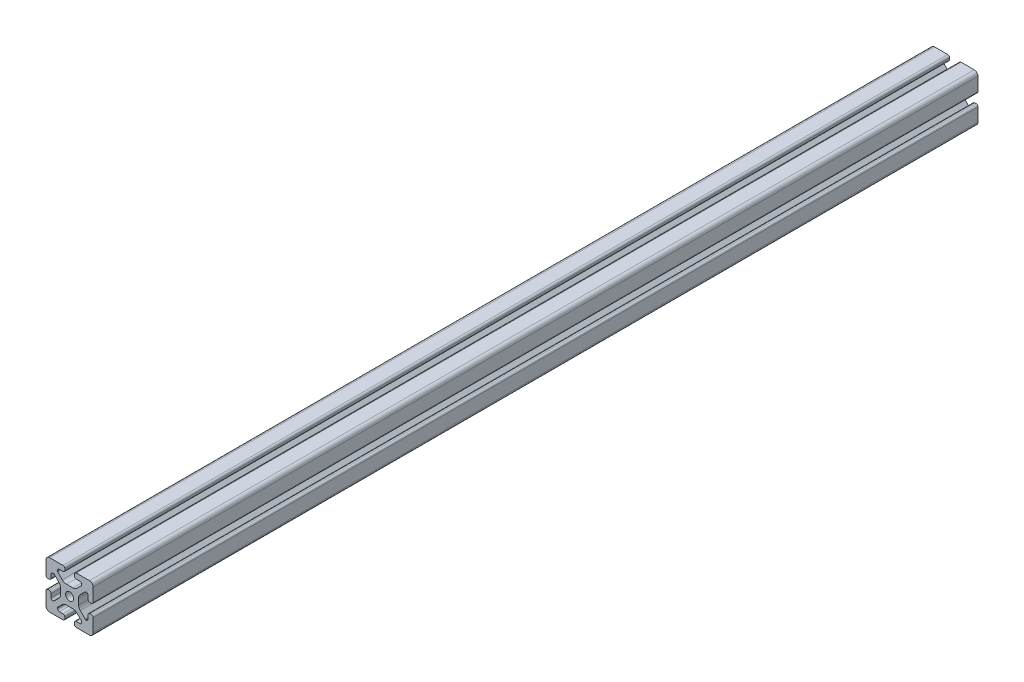
SolidWorks part; units mm, degrees
material "6061 Alloy"
ref_plane "Front Plane" through (0, 0, 0) normal (0, 0, 1) x (1, 0, 0)
ref_plane "Top Plane" through (0, 0, 0) normal (0, 1, 0) x (1, 0, 0)
ref_plane "Right Plane" through (0, 0, 0) normal (1, 0, 0) x (0, 0, -1)
sketch "Sketch1" plane through (0, 0, 0) normal (0, 0, 1) x (1, 0, 0)
  line L0 (0, 19.7407) -> (0, -19.7407) construction
  line L1 (19.0335, 0) -> (-20.7246, 0) construction
  line L2 (-8.715, -15.5246) -> (-5.63, -15.5246)
  line L3 (-10.285, -13.9546) -> (-10.285, -13.4925)
  line L4 (-6.2171, -9.1098) -> (-10.0624, -12.9551)
  line L5 (2.7773, -7.685) -> (-2.7773, -7.685)
  line L6 (10.0624, -12.9551) -> (6.2171, -9.1098)
  line L7 (10.285, -13.9546) -> (10.285, -13.4925)
  line L8 (5.63, -15.5246) -> (8.715, -15.5246)
  line L9 (4.06, -18.43) -> (4.06, -17.0946)
  line L10 (-4.06, -18.43) -> (-4.06, -17.0946)
  line L11 (15.68, -8.7154) -> (15.68, -5.63)
  line L12 (-14.11, -10.2854) -> (-13.8169, -10.2854)
  line L13 (20, -16.83) -> (20, -5.63)
  line L14 (20, 5.63) -> (20, 13.0011)
  line L15 (-16.83, 20) -> (-5.63, 20)
  line L16 (5.63, 20) -> (12.9796, 20)
  line L18 (-8.715, 15.5246) -> (-5.63, 15.5246)
  line L19 (-20, -17.0184) -> (-20, -5.7579)
  line L20 (-20, 5.573) -> (-20, 13.0045)
  line L21 (-15.68, -8.7154) -> (-15.68, -5.7579)
  line L23 (-16.6746, -20) -> (-5.63, -20)
  line L24 (5.63, -20) -> (13, -20)
  line L53 (14.11, -10.2854) -> (13.6201, -10.2854)
  line L54 (13.1637, -9.947) -> (9.0762, -5.8595)
  line L55 (7.685, -2.5008) -> (7.685, 2.5008)
  line L56 (9.0762, 5.8595) -> (13.2795, 10.0628)
  line L57 (13.8169, 10.2854) -> (14.11, 10.2854)
  line L58 (15.68, 8.7154) -> (15.68, 5.63)
  line L59 (17.25, 4.06) -> (18.43, 4.06)
  line L61 (20, 13.0011) -> (20, 16.83)
  line L62 (16.83, 20) -> (12.9796, 20)
  line L64 (4.06, 18.43) -> (4.06, 17.0946)
  line L65 (5.63, 15.5246) -> (8.715, 15.5246)
  line L66 (10.285, 13.9546) -> (10.285, 13.4925)
  line L67 (10.0624, 12.9551) -> (6.2171, 9.1098)
  line L68 (2.7773, 7.685) -> (-2.7773, 7.685)
  line L69 (-6.2171, 9.1098) -> (-10.0624, 12.9551)
  line L70 (-10.285, 13.4925) -> (-10.285, 13.9546)
  line L72 (-4.06, 17.0946) -> (-4.06, 18.43)
  line L75 (-20, 16.83) -> (-20, 13.0045)
  line L77 (-18.43, 4.003) -> (-17.25, 4.003)
  line L78 (-15.68, 5.573) -> (-15.68, 8.4757)
  line L79 (-14.0552, 10.0447) -> (-13.7199, 10.033)
  line L80 (-13.0405, 9.8238) -> (-9.0762, 5.8595)
  line L81 (-7.685, 2.5008) -> (-7.685, -2.5008)
  line L82 (-9.0762, -5.8595) -> (-13.2795, -10.0628)
  line L85 (-17.25, -4.1204) -> (-18.43, -4.1204)
  line L100 (13, -20) -> (16.83, -20)
  line L103 (18.43, -4.06) -> (17.25, -4.06)
  arc A0 (-5.63, -15.5246) -> (-4.06, -17.0946) centre (-5.63, -17.0946) cw
  arc A1 (-8.715, -15.5246) -> (-10.285, -13.9546) centre (-8.715, -13.9546) cw
  arc A2 (-10.285, -13.4925) -> (-10.0624, -12.9551) centre (-9.525, -13.4925) cw
  arc A3 (-6.2171, -9.1098) -> (-2.7773, -7.685) centre (-2.7773, -12.5496) cw
  arc A4 (2.7773, -7.685) -> (6.2171, -9.1098) centre (2.7773, -12.5496) cw
  arc A5 (10.0624, -12.9551) -> (10.285, -13.4925) centre (9.525, -13.4925) cw
  arc A6 (10.285, -13.9546) -> (8.715, -15.5246) centre (8.715, -13.9546) cw
  arc A7 (4.06, -17.0946) -> (5.63, -15.5246) centre (5.63, -17.0946) cw
  arc A8 (5.63, -20) -> (4.06, -18.43) centre (5.63, -18.43) cw
  arc A9 (-4.06, -18.43) -> (-5.63, -20) centre (-5.63, -18.43) cw
  circle A45 centre (0, 0) radius 3.4
  arc A46 (17.25, -4.06) -> (15.68, -5.63) centre (17.25, -5.63) ccw
  arc A47 (14.11, -10.2854) -> (15.68, -8.7154) centre (14.11, -8.7154) ccw
  arc A48 (13.1637, -9.947) -> (13.6201, -10.2854) centre (13.8117, -9.55) ccw
  arc A49 (7.685, -2.5008) -> (9.0762, -5.8595) centre (12.435, -2.5008) ccw
  arc A50 (9.0762, 5.8595) -> (7.685, 2.5008) centre (12.435, 2.5008) ccw
  arc A51 (13.8169, 10.2854) -> (13.2795, 10.0628) centre (13.8169, 9.5254) ccw
  arc A52 (15.68, 8.7154) -> (14.11, 10.2854) centre (14.11, 8.7154) ccw
  arc A53 (15.68, 5.63) -> (17.25, 4.06) centre (17.25, 5.63) ccw
  arc A54 (18.43, 4.06) -> (20, 5.63) centre (18.43, 5.63) ccw
  arc A55 (20, 16.83) -> (16.83, 20) centre (16.83, 16.83) ccw
  arc A56 (5.63, 20) -> (4.06, 18.43) centre (5.63, 18.43) ccw
  arc A57 (4.06, 17.0946) -> (5.63, 15.5246) centre (5.63, 17.0946) ccw
  arc A58 (10.285, 13.9546) -> (8.715, 15.5246) centre (8.715, 13.9546) ccw
  arc A59 (10.0624, 12.9551) -> (10.285, 13.4925) centre (9.525, 13.4925) ccw
  arc A60 (2.7773, 7.685) -> (6.2171, 9.1098) centre (2.7773, 12.5496) ccw
  arc A61 (-6.2171, 9.1098) -> (-2.7773, 7.685) centre (-2.7773, 12.5496) ccw
  arc A62 (-10.285, 13.4925) -> (-10.0624, 12.9551) centre (-9.525, 13.4925) ccw
  arc A63 (-8.715, 15.5246) -> (-10.285, 13.9546) centre (-8.715, 13.9546) ccw
  arc A64 (-5.63, 15.5246) -> (-4.06, 17.0946) centre (-5.63, 17.0946) ccw
  arc A65 (-4.06, 18.43) -> (-5.63, 20) centre (-5.63, 18.43) ccw
  arc A66 (-16.83, 20) -> (-20, 16.83) centre (-16.83, 16.83) ccw
  arc A67 (-20, 5.573) -> (-18.43, 4.003) centre (-18.43, 5.573) ccw
  arc A68 (-17.25, 4.003) -> (-15.68, 5.573) centre (-17.25, 5.573) ccw
  arc A69 (-14.0552, 10.0447) -> (-15.68, 8.4757) centre (-14.11, 8.4757) ccw
  arc A70 (-13.0405, 9.8238) -> (-13.7199, 10.033) centre (-13.5779, 9.2864) ccw
  arc A71 (-7.685, 2.5008) -> (-9.0762, 5.8595) centre (-12.435, 2.5008) ccw
  arc A72 (-9.0762, -5.8595) -> (-7.685, -2.5008) centre (-12.435, -2.5008) ccw
  arc A73 (-13.8169, -10.2854) -> (-13.2795, -10.0628) centre (-13.8169, -9.5254) ccw
  arc A74 (-15.68, -8.7154) -> (-14.11, -10.2854) centre (-14.11, -8.7154) ccw
  arc A75 (-15.68, -5.7579) -> (-17.25, -4.1204) centre (-17.2485, -5.6904) ccw
  arc A76 (-18.43, -4.1204) -> (-20, -5.7579) centre (-18.4315, -5.6904) ccw
  arc A77 (-20, -17.0184) -> (-16.6746, -20) centre (-16.8354, -16.8341) ccw
  arc A88 (16.83, -20) -> (20, -16.83) centre (16.83, -16.83) ccw
  arc A89 (20, -5.63) -> (18.43, -4.06) centre (18.43, -5.63) ccw
  dimension "D2" = 6.8
  dimension "D7" = 20.57
  dimension "D1" = 40
  dimension "D3" = 4.32
  dimension "D4" = 15.37
  dimension "D5" = 20
  dimension "D6" = 4.32
  dimension "D9" = 15.37
extrude "Extrude1" add sketch "Sketch1" against normal blind 750
